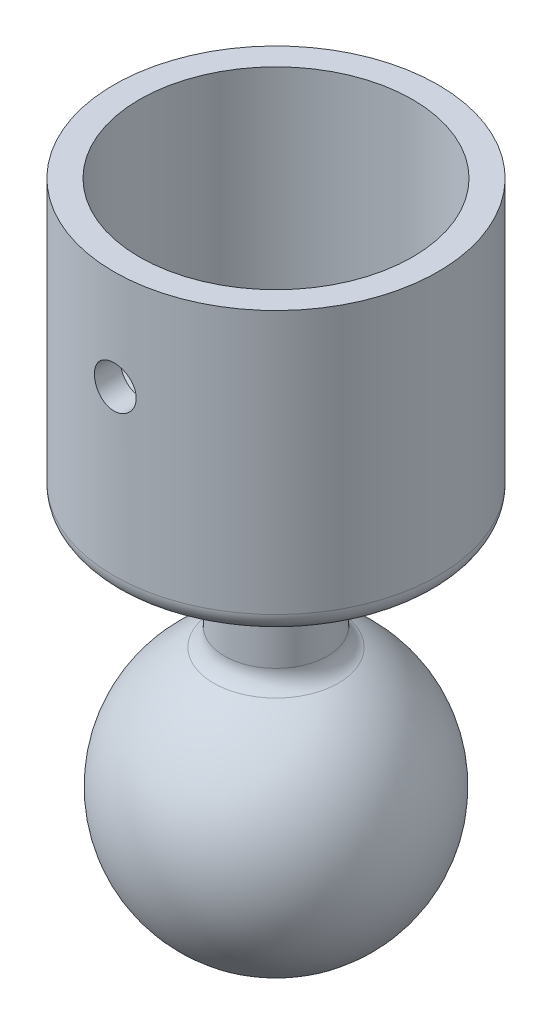
SolidWorks part; units mm, degrees
ref_plane "Front Plane" through (0, 0, 0) normal (0, 0, 1) x (1, 0, 0)
ref_plane "Top Plane" through (0, 0, 0) normal (0, 1, 0) x (1, 0, 0)
ref_plane "Right Plane" through (0, 0, 0) normal (1, 0, 0) x (0, 0, -1)
sketch "Sketch1" plane through (0, 0, 0) normal (0, 1, 0) x (1, 0, 0)
  line L0 (0, 16.75) -> (0, -16.75) construction
  line L1 (0, 16.75) -> (0, -16.75)
  arc A0 (0, -16.75) -> (0, 16.75) centre (0, 0) ccw
  dimension "D1" = 16.75
revolve "Revolve3" add sketch "Sketch1" angle 360 about L0
sketch "Sketch2" plane through (0, 0, 0) normal (0, 1, 0) x (1, 0, 0)
  circle A0 centre (0, 0) radius 6.35
  dimension "D1" = 12.7
extrude "Boss-Extrude1" add sketch "Sketch2" along normal blind 30
sketch "Sketch3" plane through (0, 30, 0) normal (0, 1, 0) x (1, 0, 0)
  circle A0 centre (0, 0) radius 20
extrude "Boss-Extrude3" add sketch "Sketch3" along normal blind 10
fillet "Fillet1" radius 3.9 1 edges at (0, 30, 6.35)
sketch "Sketch4" plane through (0, 40, 0) normal (0, 1, 0) x (1, 0, 0)
  circle A0 centre (0, 0) radius 20
  circle A1 centre (0, 0) radius 16.85
extrude "Boss-Extrude4" add sketch "Sketch4" along normal blind 25
fillet "Fillet2" radius 2.5 1 edges at (0, 30, 20)
fillet "Fillet3" radius 2.5 1 edges at (0, 15.4997, -6.35)
sketch "Sketch5" plane through (0, 0, 0) normal (0, 0, 1) x (1, 0, 0)
  line L0 (16.85, 40) -> (-16.85, 40) construction
  circle A0 centre (0, 52.7) radius 2.5797
  dimension "D1" = 12.7
extrude "Cut-Extrude1" cut sketch "Sketch5" along normal through all
